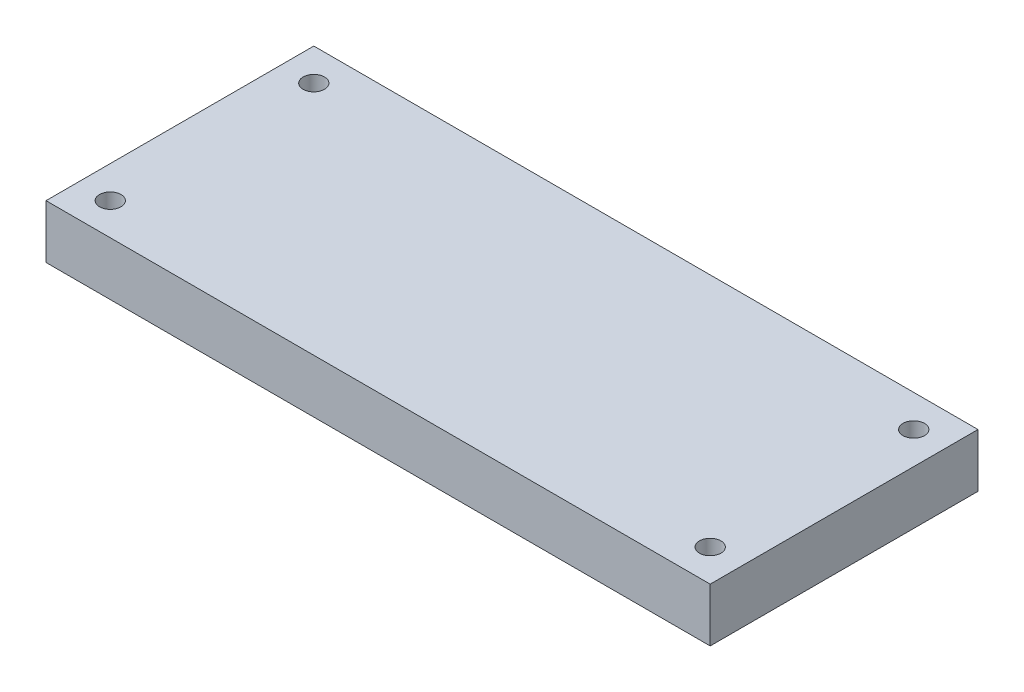
SolidWorks part; units mm, degrees
ref_plane "Piano frontale" through (0, 0, 0) normal (0, 0, 1) x (1, 0, 0)
ref_plane "Piano superiore" through (0, 0, 0) normal (0, 1, 0) x (1, 0, 0)
ref_plane "Piano destro" through (0, 0, 0) normal (1, 0, 0) x (0, 0, -1)
sketch "Schizzo1" plane through (0, 0, 0) normal (0, 1, 0) x (1, 0, 0)
  line L1 (-31, -12.5) -> (31, -12.5)
  line L2 (-31, -12.5) -> (-31, 12.5)
  line L3 (-31, 12.5) -> (31, 12.5)
  line L4 (31, -12.5) -> (31, 12.5)
  line L5 (-31, -12.5) -> (31, 12.5) construction
  line L6 (-31, 12.5) -> (31, -12.5) construction
  point P0 (0, 0)
  dimension "D1" = 62
  dimension "D2" = 25
extrude "Estrusione-Estrusione1" add sketch "Schizzo1" along normal blind 5
sketch "Schizzo2" plane through (0, 5, 0) normal (0, 1, 0) x (1, 0, 0)
  line L0 (31, 12.5) -> (-31, 12.5) construction
  line L1 (-31, 12.5) -> (-31, -12.5) construction
  line L2 (31, -12.5) -> (31, 12.5) construction
  line L3 (-31, -12.5) -> (31, -12.5) construction
  circle A0 centre (-28, 9.5) radius 1
  circle A1 centre (-28, -9.5) radius 1
  circle A2 centre (28, 9.5) radius 1
  circle A3 centre (28, -9.5) radius 1
  dimension "D1" = 2
  dimension "D2" = 2
  dimension "D3" = 2
  dimension "D4" = 2
  dimension "D5" = 3
  dimension "D6" = 3
  dimension "D7" = 3
  dimension "D8" = 3
  dimension "D9" = 3
  dimension "D10" = 3
  dimension "D11" = 3
  dimension "D12" = 3
extrude "Taglio-Estrusione1" cut sketch "Schizzo2" against normal blind 5
